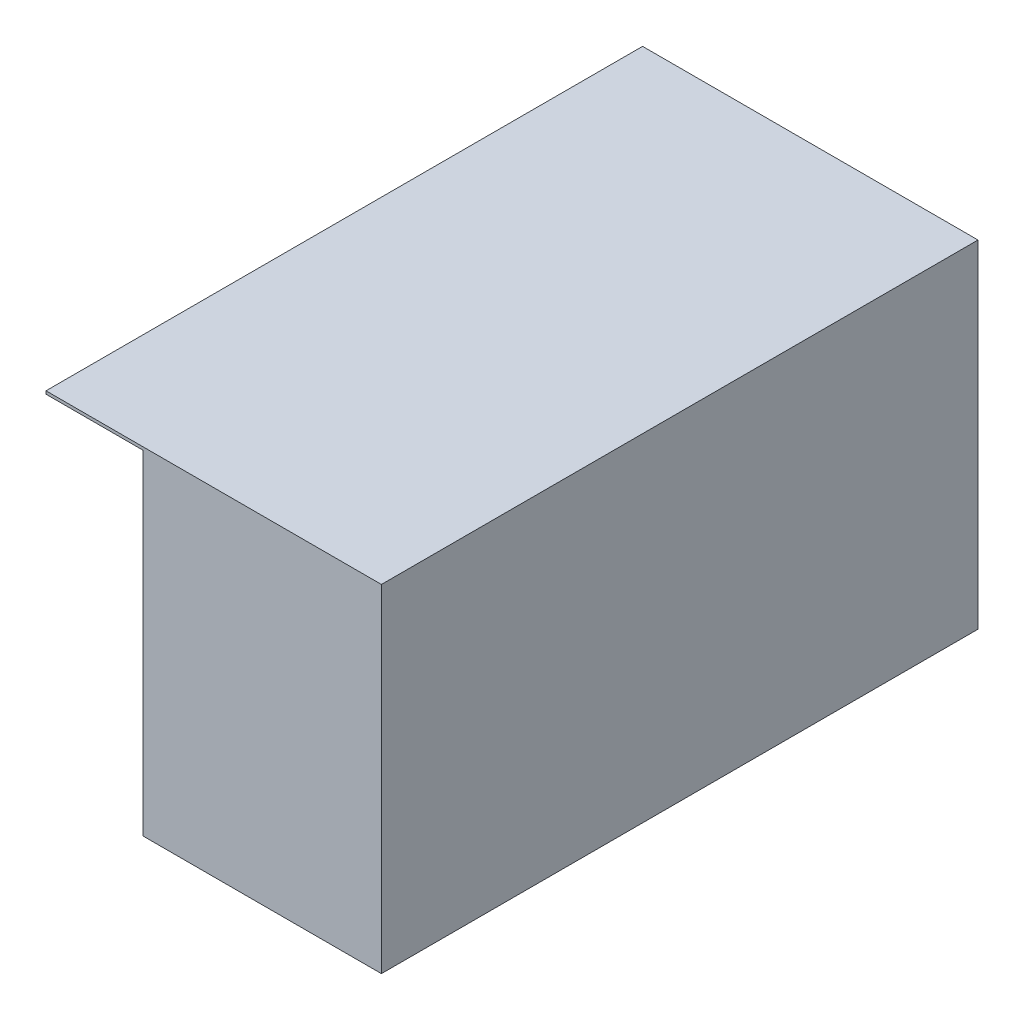
SolidWorks part; units mm, degrees
ref_plane "Front Plane" through (0, 0, 0) normal (0, 0, 1) x (1, 0, 0)
ref_plane "Top Plane" through (0, 0, 0) normal (0, 1, 0) x (1, 0, 0)
ref_plane "Right Plane" through (0, 0, 0) normal (1, 0, 0) x (0, 0, -1)
sketch "Sketch2" plane through (0, 0, 0) normal (0, 0, 1) x (1, 0, 0)
  line L1 (-32.963, -11.4815) -> (47.037, -11.4815)
  line L2 (-32.963, -11.4815) -> (-32.963, 100.5185)
  line L3 (-32.963, 100.5185) -> (47.037, 100.5185)
  line L4 (47.037, -11.4815) -> (47.037, 100.5185)
  dimension "D1" = 80
  dimension "D2" = 112
extrude "Boss-Extrude2" add sketch "Sketch2" along normal blind 200
sketch "Sketch3" plane through (-32.963, 0, 0) normal (-1, 0, 0) x (0, 0, 1)
  line L0 (200, -11.4815) -> (0, -11.4815) construction
  line L1 (191.093, -11.4815) -> (147.3344, -11.4815)
  line L2 (191.093, -11.4815) -> (191.093, 61.5038)
  line L3 (191.093, 61.5038) -> (147.3344, 61.5038)
  line L4 (147.3344, -11.4815) -> (147.3344, 61.5038)
extrude "Cut-Extrude1" cut sketch "Sketch3" against normal blind 70
sketch "Sketch4" plane through (0, -11.4815, 0) normal (0, -1, 0) x (1, 0, 0)
  line L1 (43.1751, 3.0699) -> (-29.8462, 3.0699)
  line L2 (43.1751, 3.0699) -> (43.1751, 195.6822)
  line L3 (43.1751, 195.6822) -> (-29.8462, 195.6822)
  line L4 (-29.8462, 3.0699) -> (-29.8462, 195.6822)
extrude "Cut-Extrude2" cut sketch "Sketch4" against normal blind 110
sketch "Sketch5" plane through (-32.963, 0, 0) normal (-1, 0, 0) x (0, 0, 1)
  line L1 (33.7667, 27.9516) -> (89.2806, 27.9516)
  line L2 (33.7667, 27.9516) -> (33.7667, 32.3113)
  line L3 (33.7667, 32.3113) -> (89.2806, 32.3113)
  line L4 (89.2806, 27.9516) -> (89.2806, 32.3113)
extrude "Boss-Extrude3" add sketch "Sketch5" along normal blind 30
sketch "Sketch6" plane through (-32.963, 0, 0) normal (-1, 0, 0) x (0, 0, 1)
  text T0 "CHECK POINT" font "Century Gothic" height in points 72
extrude "Boss-Extrude4" add sketch "Sketch6" along normal blind 2.5
sketch "Sketch7" plane through (0, 100.5185, 0) normal (0, 1, 0) x (1, 0, 0)
  line L1 (47.037, -200) -> (-65.4074, -200)
  line L2 (47.037, -200) -> (47.037, 0)
  line L3 (47.037, 0) -> (-65.4074, 0)
  line L4 (-65.4074, -200) -> (-65.4074, 0)
extrude "Boss-Extrude5" add sketch "Sketch7" along normal blind 1
sketch "Sketch8" plane through (0, -11.4815, 0) normal (0, -1, 0) x (1, 0, 0)
  line L1 (47.037, 0) -> (-32.963, 0)
  line L2 (47.037, 0) -> (47.037, 200)
  line L3 (47.037, 200) -> (-32.963, 200)
  line L4 (-32.963, 0) -> (-32.963, 200)
extrude "Boss-Extrude6" add sketch "Sketch8" against normal blind 0.5
sketch "Sketch9" plane through (0, 0, 89.2806) normal (0, 0, 1) x (1, 0, 0)
  line L1 (-62.5823, 28.3557) -> (-33.3626, 28.3557)
  line L2 (-62.5823, 28.3557) -> (-62.5823, 31.8751)
  line L3 (-62.5823, 31.8751) -> (-33.3626, 31.8751)
  line L4 (-33.3626, 28.3557) -> (-33.3626, 31.8751)
extrude "Cut-Extrude3" cut sketch "Sketch9" against normal blind 60
